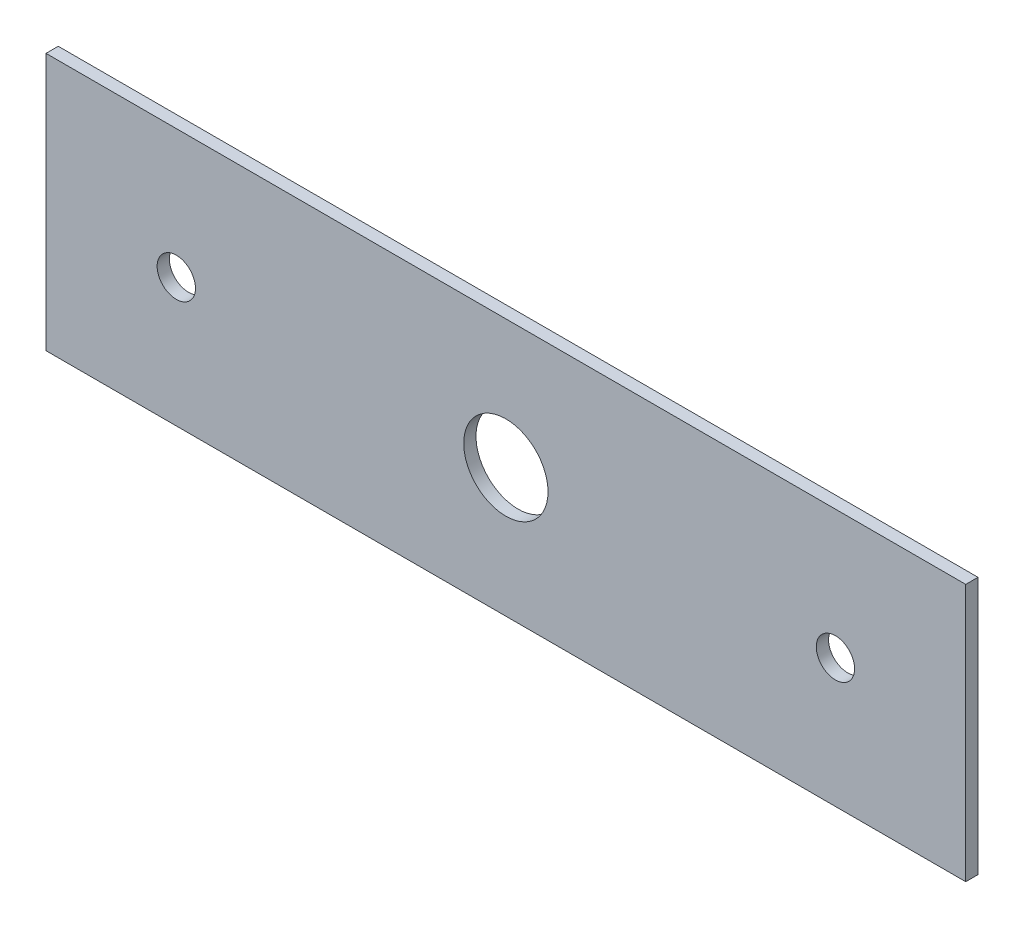
SolidWorks part; units mm, degrees
ref_plane "Front Plane" through (0, 0, 0) normal (0, 0, 1) x (1, 0, 0)
ref_plane "Top Plane" through (0, 0, 0) normal (0, 1, 0) x (1, 0, 0)
ref_plane "Right Plane" through (0, 0, 0) normal (1, 0, 0) x (0, 0, -1)
sketch "Sketch1" plane through (0, 0, 0) normal (0, 0, 1) x (1, 0, 0)
  line L1 (-60, 16.8) -> (60, 16.8)
  line L2 (-60, 16.8) -> (-60, -16.8)
  line L3 (-60, -16.8) -> (60, -16.8)
  line L4 (60, 16.8) -> (60, -16.8)
  line L5 (-60, 16.8) -> (60, -16.8) construction
  line L6 (-60, -16.8) -> (60, 16.8) construction
  circle A0 centre (0, 0) radius 5.5
  circle A1 centre (-43, 0) radius 2.5
  circle A2 centre (43, 0) radius 2.5
  point P0 (0, 0)
  dimension "D3" = 43
  dimension "D4" = 43
  dimension "D1" = 120
  dimension "D2" = 33.6
extrude "Boss-Extrude1" add sketch "Sketch1" along normal blind 1.6
